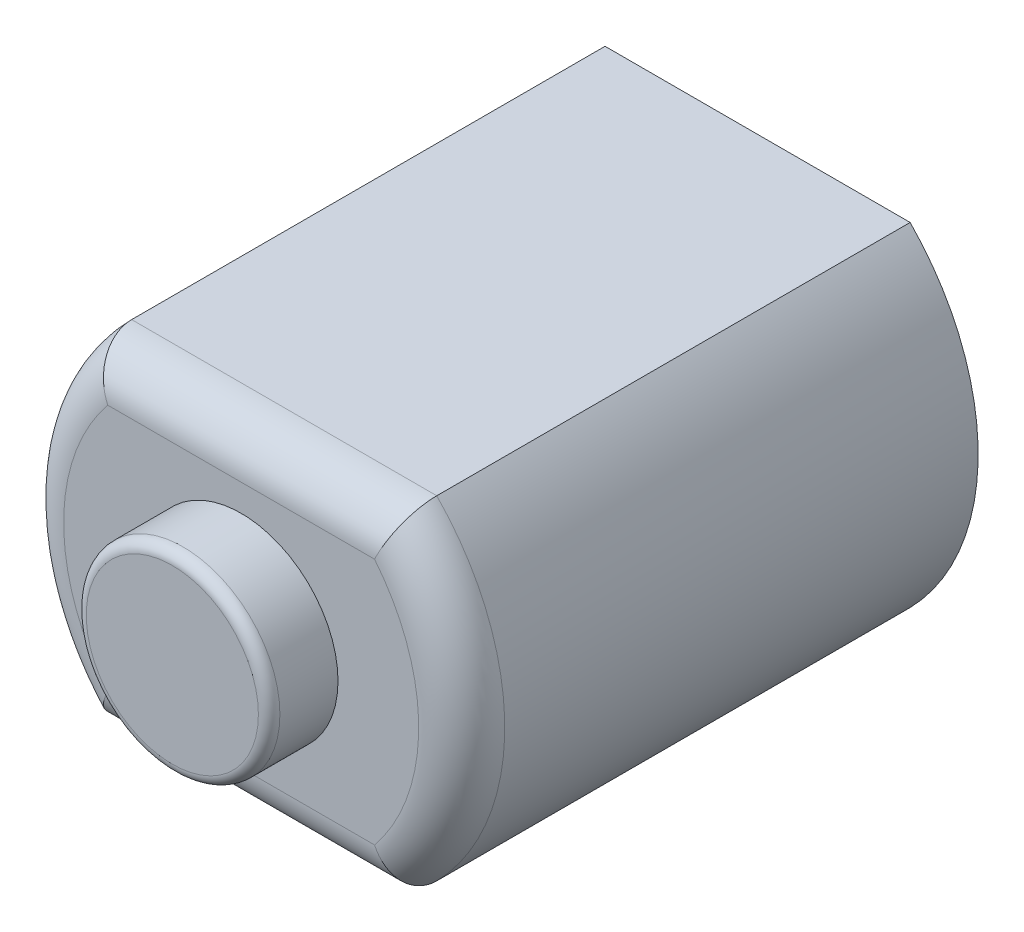
SolidWorks part; units mm, degrees
material "Aleación 1060"
ref_plane "Alzado" through (0, 0, 0) normal (0, 0, 1) x (1, 0, 0)
ref_plane "Planta" through (0, 0, 0) normal (0, 1, 0) x (1, 0, 0)
ref_plane "Vista lateral" through (0, 0, 0) normal (1, 0, 0) x (0, 0, -1)
sketch "Croquis1" plane through (0, 0, 0) normal (0, 0, 1) x (1, 0, 0)
  line L0 (0, 0) -> (0, 7.75) construction
  line L1 (7.09, 7.75) -> (-7.09, 7.75)
  line L2 (0, 0) -> (-10.25, 0) construction
  line L3 (7.09, -7.75) -> (-7.09, -7.75)
  arc A0 (-7.09, 7.75) -> (-7.09, -7.75) centre (0.8336, 0) ccw
  arc A1 (7.09, 7.75) -> (7.09, -7.75) centre (-0.8336, 0) cw
  point P9 (0, -7.75)
  dimension "D1" = 7.09
  dimension "D2" = 3.16
  dimension "D3" = 15.5
extrude "Saliente-Extruir1" add sketch "Croquis1" along normal blind 24
fillet "Redondeo1" radius 2 4 edges at (0, 7.75, 24) (10.25, 0, 24) (0, -7.75, 24) (-10.25, 0, 24)
sketch "Croquis2" plane through (0, 0, 24) normal (0, 0, 1) x (1, 0, 0)
  line L0 (-10.25, 0) -> (10.25, 0) construction
  line L1 (0, 7.75) -> (0, -7.75) construction
  line L2 (-7.09, 7.75) -> (7.09, 7.75) construction
  line L3 (7.09, -7.75) -> (-7.09, -7.75) construction
  arc A0 (-7.09, 7.75) -> (-7.09, -7.75) centre (0.8336, 0) ccw construction
  arc A1 (7.09, -7.75) -> (7.09, 7.75) centre (-0.8336, 0) ccw construction
  circle A2 centre (0, 0) radius 4.5
  dimension "D1" = 9
extrude "Saliente-Extruir2" add sketch "Croquis2" along normal blind 3.2
fillet "Redondeo2" radius 0.5 1 edges at (4.5, 0, 27.2)
